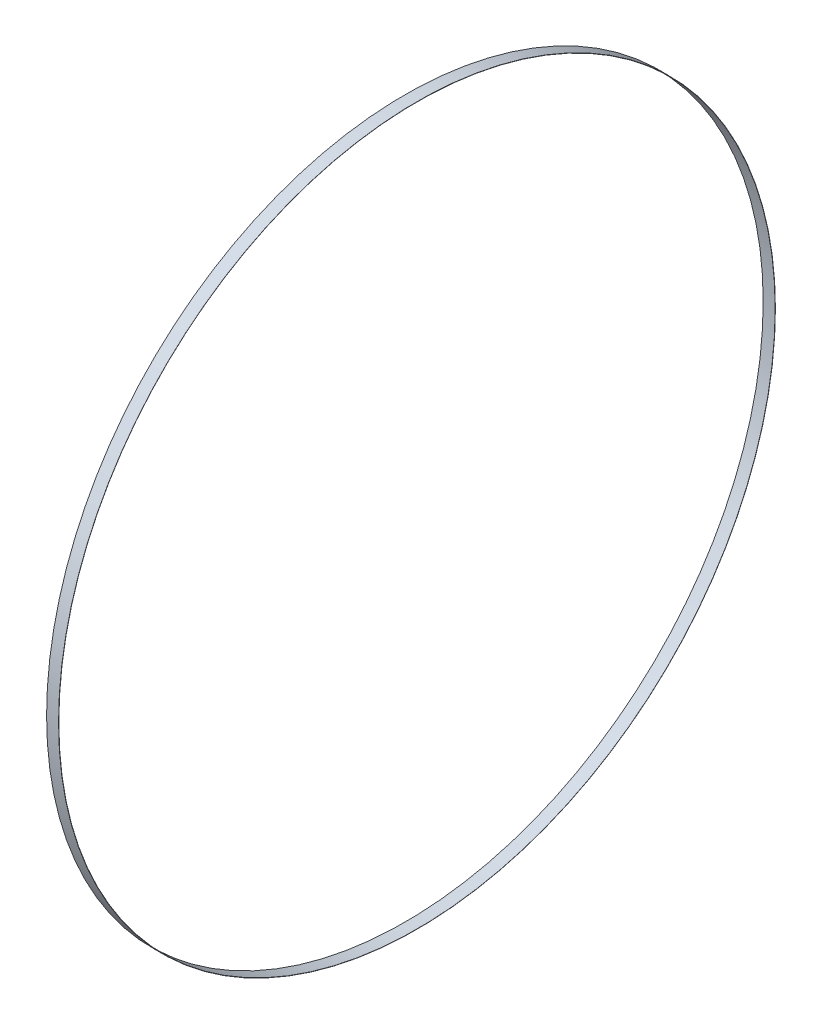
SolidWorks part; units mm, degrees
material "Клей"
ref_plane "Спереди" through (0, 0, 0) normal (0, 0, 1) x (1, 0, 0)
ref_plane "Сверху" through (0, 0, 0) normal (0, 1, 0) x (1, 0, 0)
ref_plane "Справа" through (0, 0, 0) normal (1, 0, 0) x (0, 0, -1)
sketch "Эскиз1" plane through (0, 0, 0) normal (0, 0, 1) x (1, 0, 0)
  line L0 (0, 0) -> (4241.9402, 0) construction
  line L2 (0, -1494.5) -> (50, -1494.5)
  line L3 (0, -1494.5) -> (0, -1495.5)
  line L4 (0, -1495.5) -> (50, -1495.5)
  line L5 (50, -1494.5) -> (50, -1495.5)
  dimension "D1" = 1495.5
  dimension "D2" = 50
  dimension "D3" = 1
revolve "Повернуть1" add sketch "Эскиз1" angle 360 about L0
